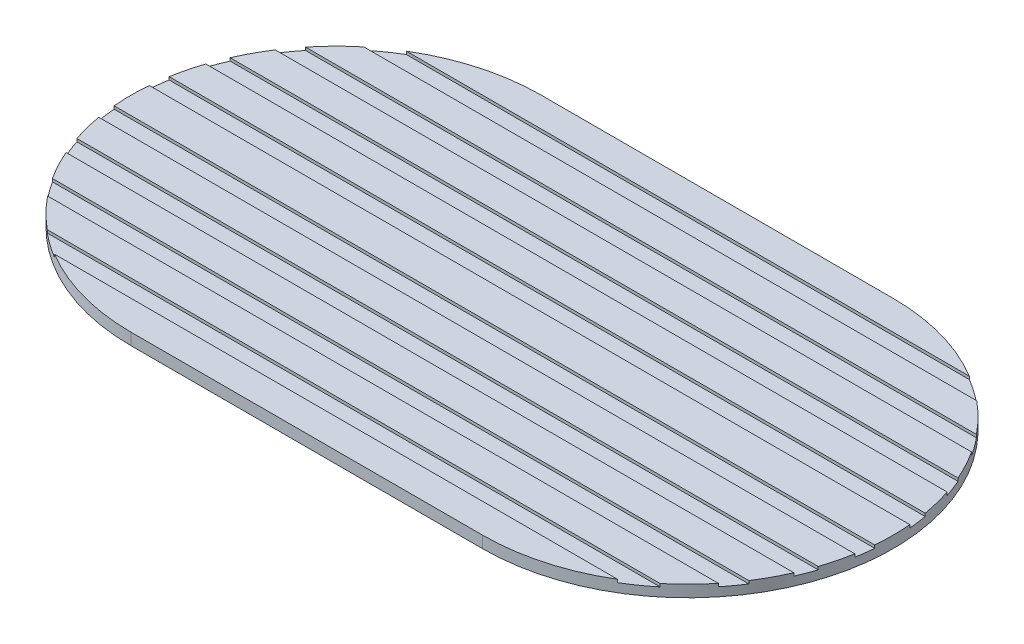
SolidWorks part; units mm, degrees
material "Oak"
ref_plane "Front Plane" through (0, 0, 0) normal (0, 0, 1) x (1, 0, 0)
ref_plane "Top Plane" through (0, 0, 0) normal (0, 1, 0) x (1, 0, 0)
ref_plane "Right Plane" through (0, 0, 0) normal (1, 0, 0) x (0, 0, -1)
sketch "Sketch1" plane through (0, 0, 0) normal (0, 1, 0) x (1, 0, 0)
  line L0 (0, 35) -> (-60, 35)
  line L1 (0, -35) -> (-60, -35)
  arc A0 (0, -35) -> (0, 35) centre (0, 0) ccw
  arc A1 (-60, 35) -> (-60, -35) centre (-60, 0) ccw
extrude "Boss-Extrude1" add sketch "Sketch1" along normal blind 2
sketch "Sketch2" plane through (0, 2, 0) normal (0, 1, 0) x (1, 0, 0)
  line L0 (-30, 35) -> (-30, -35) construction
  line L1 (0, 35) -> (-60, 35) construction
  line L2 (-60, -35) -> (0, -35) construction
  line L3 (-97.6347, 30) -> (39.6516, 30) construction
  line L4 (-99.3827, 27) -> (39.6516, 27) construction
  line L5 (-85.802, 30) -> (25.1297, 30)
  line L6 (25.1297, 30) -> (25.1297, 27)
  line L7 (25.1297, 27) -> (-85.802, 27)
  line L8 (-85.802, 30) -> (-85.802, 27)
  line L9 (-99.3827, 0) -> (43.4166, 0) construction
  line L14 (-99.3827, 22) -> (39.6516, 22) construction
  line L15 (-97.6347, 19) -> (35.8867, 19) construction
  line L16 (-92.2562, 22) -> (-92.2562, 19)
  line L17 (-92.2562, 19) -> (32.2562, 19)
  line L18 (32.2562, 19) -> (32.2562, 22)
  line L19 (32.2562, 22) -> (-92.2562, 22)
  line L20 (-114.1736, 14) -> (39.6516, 14) construction
  line L21 (-99.3827, 11) -> (37.3658, 11) construction
  line L22 (-95.6178, 14) -> (-95.6178, 11)
  line L23 (-95.6178, 11) -> (35.8867, 11)
  line L24 (35.8867, 11) -> (35.8867, 14)
  line L25 (35.8867, 14) -> (-95.6178, 14)
  line L26 (-101.3997, 6) -> (40.8618, 6) construction
  line L27 (-99.3827, 3) -> (40.8618, 3) construction
  line L28 (-95.6178, 6) -> (-95.6178, 3)
  line L29 (-95.6178, 3) -> (38.307, 3)
  line L30 (38.307, 3) -> (38.307, 6)
  line L31 (38.307, 6) -> (-95.6178, 6)
  line L32 (38.307, -3) -> (38.307, -6)
  line L33 (-95.6178, -3) -> (38.307, -3)
  line L34 (-95.6178, -6) -> (-95.6178, -3)
  line L35 (38.307, -6) -> (-95.6178, -6)
  line L36 (35.8867, -11) -> (35.8867, -14)
  line L37 (-95.6178, -11) -> (35.8867, -11)
  line L38 (-95.6178, -14) -> (-95.6178, -11)
  line L39 (35.8867, -14) -> (-95.6178, -14)
  line L40 (32.2562, -19) -> (32.2562, -22)
  line L41 (-92.2562, -19) -> (32.2562, -19)
  line L42 (-92.2562, -22) -> (-92.2562, -19)
  line L43 (32.2562, -22) -> (-92.2562, -22)
  line L44 (-85.802, -30) -> (25.1297, -30)
  line L45 (25.1297, -30) -> (25.1297, -27)
  line L46 (25.1297, -27) -> (-85.802, -27)
  line L47 (-85.802, -30) -> (-85.802, -27)
  dimension "D1" = 5
  dimension "D2" = 3
  dimension "D3" = 5
  dimension "D4" = 3
  dimension "D5" = 5
  dimension "D6" = 3
  dimension "D7" = 5
  dimension "D8" = 3
extrude "Cut-Extrude1" cut sketch "Sketch2" against normal blind 0.5
